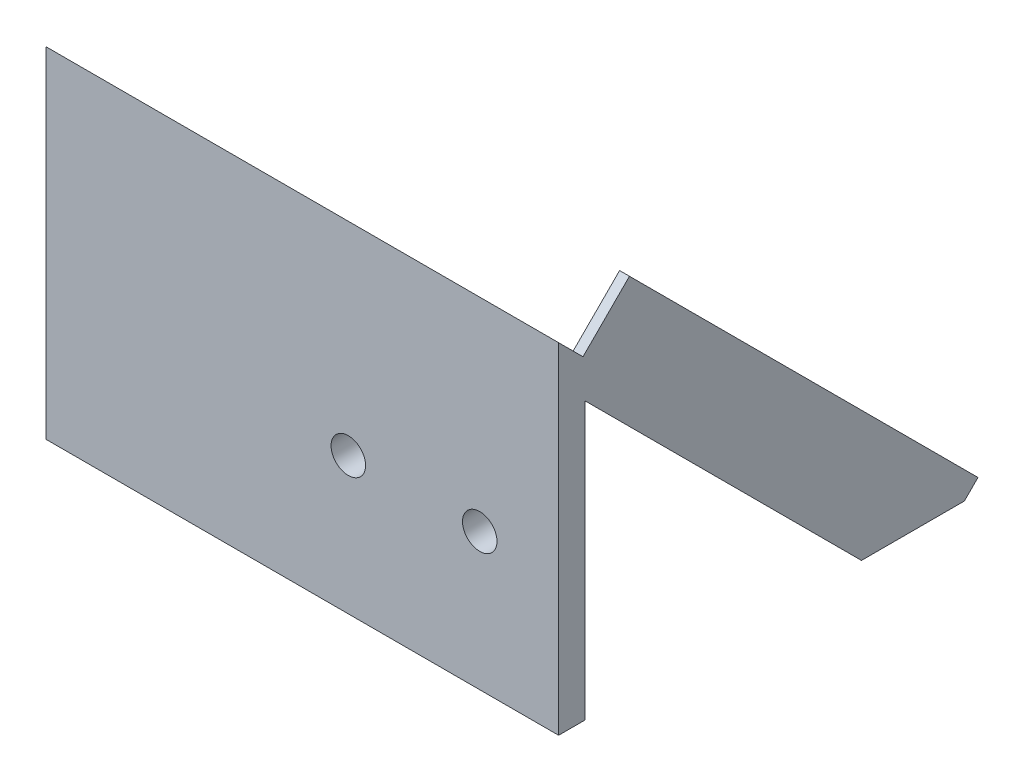
SolidWorks part; units mm, degrees
ref_plane "Front Plane" through (0, 0, 0) normal (0, 0, 1) x (1, 0, 0)
ref_plane "Top Plane" through (0, 0, 0) normal (0, 1, 0) x (1, 0, 0)
ref_plane "Right Plane" through (0, 0, 0) normal (1, 0, 0) x (0, 0, -1)
sketch "Sketch1" plane through (0, 0, 0) normal (1, 0, 0) x (0, 0, -1)
  line L0 (0, 0) -> (0, 56.74)
  line L1 (0, 56.74) -> (56.74, 0)
  line L2 (56.74, 0) -> (51.08, 0)
  line L3 (4, 0) -> (4, 47.08)
  line L4 (4, 47.08) -> (51.08, 0)
  line L5 (4, 0) -> (0, 0)
  dimension "D1" = 56.74
  dimension "D2" = 45
  dimension "D3" = 4
  dimension "D4" = 45
  dimension "D5" = 47.08
  dimension "D6" = 4.0022
extrude "Boss-Extrude1" add sketch "Sketch1" along normal blind 78
sketch "Sketch2" plane through (0, 28.37, -28.37) normal (0, 0.7071, -0.7071) x (1, 0, 0)
  line L1 (78, 40.1212) -> (76.5, 40.1212)
  line L2 (78, 40.1212) -> (78, -34.8788)
  line L3 (78, -34.8788) -> (76.5, -34.8788)
  line L4 (76.5, 40.1212) -> (76.5, -34.8788)
  dimension "D1" = 1.5
  dimension "D2" = 75
extrude "Boss-Extrude2" add sketch "Sketch2" along normal blind 10
sketch "Sketch3" plane through (0, 0, 0) normal (0, 0, 1) x (1, 0, 0)
  line L1 (78, 56.74) -> (78, 0) construction
  line L2 (78, 56.74) -> (0, 56.74) construction
  circle A0 centre (66, 25.86) radius 2.625
  circle A1 centre (46, 25.86) radius 2.625
  dimension "D1" = 30.88
  dimension "D2" = 12
  dimension "D3" = 5.25
  dimension "D4" = 20
  dimension "D5" = 30.88
  dimension "D6" = 5.25
extrude "Cut-Extrude1" cut sketch "Sketch3" against normal up to next
sketch "Sketch4" plane through (0, 0, 0) normal (0, 0, 1) x (1, 0, 0)
  line L0 (0, 56.74) -> (0, 0) construction
  line L1 (78, 0) -> (0, 0)
  line L2 (78, 0) -> (78, 5)
  line L3 (78, 5) -> (0, 5)
  line L4 (0, 0) -> (0, 5)
  dimension "D1" = 5
extrude "Cut-Extrude2" cut sketch "Sketch4" against normal through all
